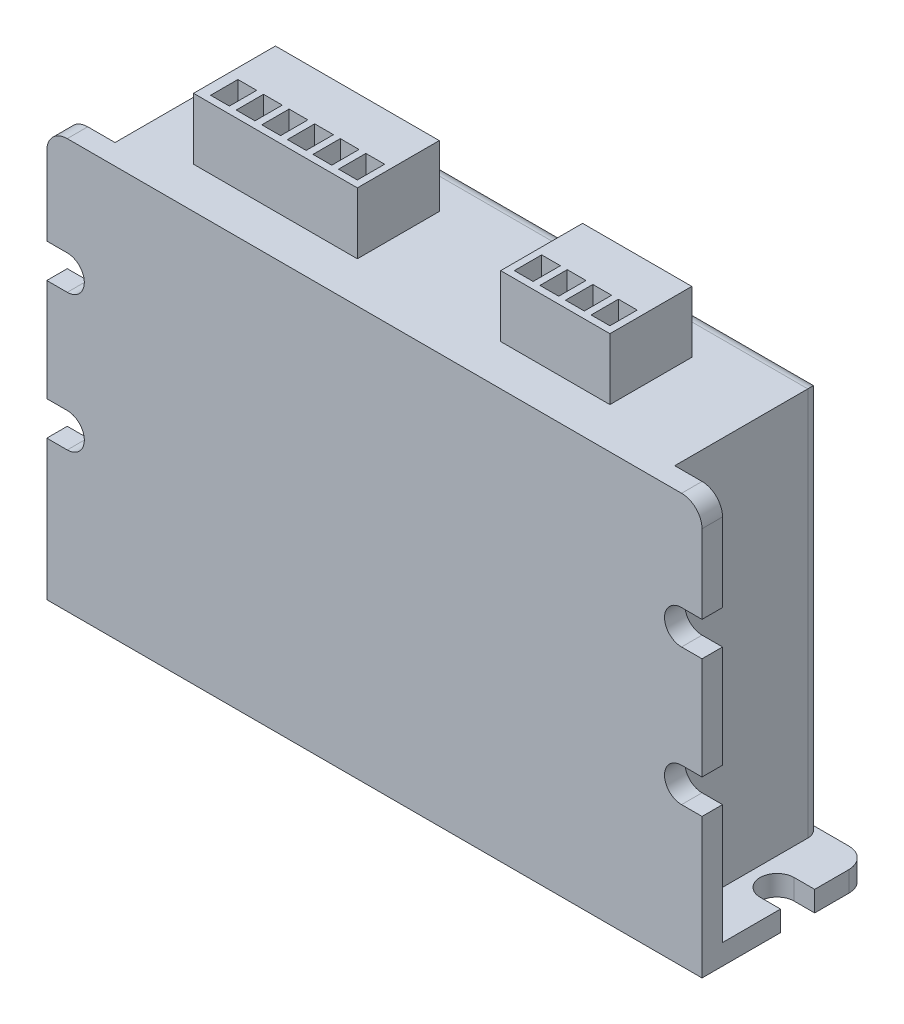
SolidWorks part; units mm, degrees
ref_plane "Front Plane" through (0, 0, 0) normal (0, 0, 1) x (1, 0, 0)
ref_plane "Top Plane" through (0, 0, 0) normal (0, 1, 0) x (1, 0, 0)
ref_plane "Right Plane" through (0, 0, 0) normal (1, 0, 0) x (0, 0, -1)
sketch "Sketch1" plane through (0, 0, 0) normal (0, 1, 0) x (1, 0, 0)
  line L1 (0, 0) -> (96, 0)
  line L2 (0, 0) -> (0, 24.5)
  line L3 (0, 24.5) -> (96, 24.5)
  line L4 (96, 0) -> (96, 24.5)
  dimension "D1" = 24.5
  dimension "D2" = 96
extrude "Boss-Extrude1" add sketch "Sketch1" along normal blind 3
sketch "Sketch2" plane through (0, 3, 0) normal (0, 1, 0) x (1, 0, 0)
  line L0 (96, 0) -> (96, 24.5) construction
  line L1 (0, 0) -> (96, 0)
  line L2 (0, 0) -> (0, 3)
  line L3 (0, 3) -> (7, 3)
  line L4 (96, 0) -> (96, 3)
  line L5 (96, 24.5) -> (0, 24.5) construction
  line L7 (7, 3) -> (7, 24.5)
  line L8 (7, 24.5) -> (89, 24.5)
  line L9 (89, 3) -> (89, 24.5)
  line L10 (96, 24.5) -> (0, 24.5) construction
  line L11 (89, 3) -> (96, 3)
  point P13 (48, 24.5)
  point P16 (48, 24.5)
  dimension "D1" = 3
  dimension "D2" = 82
extrude "Boss-Extrude2" add sketch "Sketch2" along normal blind 57
fillet "Fillet1" radius 2 3 edges at (7, 31.5, -24.5) (89, 31.5, -24.5) (48, 60, -24.5)
fillet "Fillet2" radius 3 4 edges at (0, 1.5, -24.5) (96, 1.5, -24.5) (0, 60, -1.5) (96, 60, -1.5)
sketch "Sketch3" plane through (0, 0, -3) normal (0, 0, -1) x (-1, 0, 0)
  line L0 (-93, 45.5) -> (-96, 45.5)
  line L1 (-96, 57) -> (-96, 3) construction
  line L2 (-96, 45.5) -> (-96, 40.5)
  line L3 (-96, 40.5) -> (-93, 40.5)
  line L4 (-93, 25.5) -> (-96, 25.5)
  line L5 (-96, 25.5) -> (-96, 20.5)
  line L6 (-96, 20.5) -> (-93, 20.5)
  line L7 (-3, 25.5) -> (0, 25.5)
  line L8 (0, 57) -> (0, 3) construction
  line L9 (0, 25.5) -> (0, 20.5)
  line L10 (0, 20.5) -> (-3, 20.5)
  line L11 (-3, 45.5) -> (0, 45.5)
  line L12 (0, 45.5) -> (0, 40.5)
  line L13 (0, 40.5) -> (-3, 40.5)
  line L15 (0, 0) -> (-96, 0) construction
  arc A0 (-93, 40.5) -> (-93, 45.5) centre (-93, 43) ccw
  arc A1 (-93, 20.5) -> (-93, 25.5) centre (-93, 23) ccw
  arc A2 (-3, 25.5) -> (-3, 20.5) centre (-3, 23) ccw
  arc A3 (-3, 45.5) -> (-3, 40.5) centre (-3, 43) ccw
  dimension "D1" = 2.5
  dimension "D2" = 3
  dimension "D3" = 23
  dimension "D4" = 20
extrude "Cut-Extrude1" cut sketch "Sketch3" against normal up to next
sketch "Sketch4" plane through (0, 3, 0) normal (0, 1, 0) x (1, 0, 0)
  line L0 (3, 16.5) -> (0, 16.5)
  line L1 (0, 21.5) -> (0, 3) construction
  line L2 (0, 16.5) -> (0, 11.5)
  line L3 (0, 11.5) -> (3, 11.5)
  line L4 (93, 11.5) -> (96, 11.5)
  line L5 (96, 3) -> (96, 21.5) construction
  line L6 (96, 11.5) -> (96, 16.5)
  line L7 (96, 16.5) -> (93, 16.5)
  line L8 (0, 0) -> (96, 0) construction
  arc A0 (93, 16.5) -> (93, 11.5) centre (93, 14) ccw
  arc A1 (3, 11.5) -> (3, 16.5) centre (3, 14) ccw
  dimension "D1" = 2.5
  dimension "D2" = 3
  dimension "D3" = 14
extrude "Cut-Extrude2" cut sketch "Sketch4" against normal up to next
sketch "Sketch5" plane through (0, 60, 0) normal (0, 1, 0) x (1, 0, 0)
  line L0 (89, 3) -> (89, 22.5) construction
  line L1 (76.5, 6) -> (60.5, 6)
  line L2 (76.5, 6) -> (76.5, 18)
  line L3 (76.5, 18) -> (60.5, 18)
  line L4 (60.5, 6) -> (60.5, 18)
  line L5 (39.5, 6) -> (15.5, 6)
  line L6 (39.5, 6) -> (39.5, 18)
  line L7 (39.5, 18) -> (15.5, 18)
  line L8 (15.5, 6) -> (15.5, 18)
  line L9 (7, 22.5) -> (7, 3) construction
  line L10 (3, 0) -> (93, 0) construction
  dimension "D1" = 16
  dimension "D2" = 24
  dimension "D3" = 12
  dimension "D4" = 12.5
  dimension "D5" = 8.5
  dimension "D6" = 6
extrude "Boss-Extrude3" add sketch "Sketch5" along normal blind 9
sketch "Sketch6" plane through (0, 69, 0) normal (0, 1, 0) x (1, 0, 0)
  line L0 (76.5, 6) -> (76.5, 18) construction
  line L1 (75.5, 7) -> (72.75, 7)
  line L2 (75.5, 7) -> (75.5, 11)
  line L3 (75.5, 11) -> (72.75, 11)
  line L4 (72.75, 7) -> (72.75, 11)
  line L5 (60.5, 6) -> (76.5, 6) construction
  dimension "D1" = 1
  dimension "D2" = 1
  dimension "D3" = 2.75
  dimension "D4" = 4
extrude "Cut-Extrude3" cut sketch "Sketch6" against normal blind 6
pattern_linear "LPattern1" count 4 spacing 3.75 along (-1, 0, 0) of "Cut-Extrude3"
sketch "Sketch7" plane through (0, 69, 0) normal (0, 1, 0) x (1, 0, 0)
  line L0 (39.5, 6) -> (39.5, 18) construction
  line L1 (38.5, 7) -> (35.75, 7)
  line L2 (38.5, 7) -> (38.5, 11)
  line L3 (38.5, 11) -> (35.75, 11)
  line L4 (35.75, 7) -> (35.75, 11)
  line L5 (15.5, 6) -> (39.5, 6) construction
  dimension "D1" = 2.75
  dimension "D2" = 1
  dimension "D3" = 1
  dimension "D4" = 4
extrude "Cut-Extrude4" cut sketch "Sketch7" against normal blind 6
pattern_linear "LPattern2" count 6 spacing 3.75 along (-1, 0, 0) of "Cut-Extrude4"
